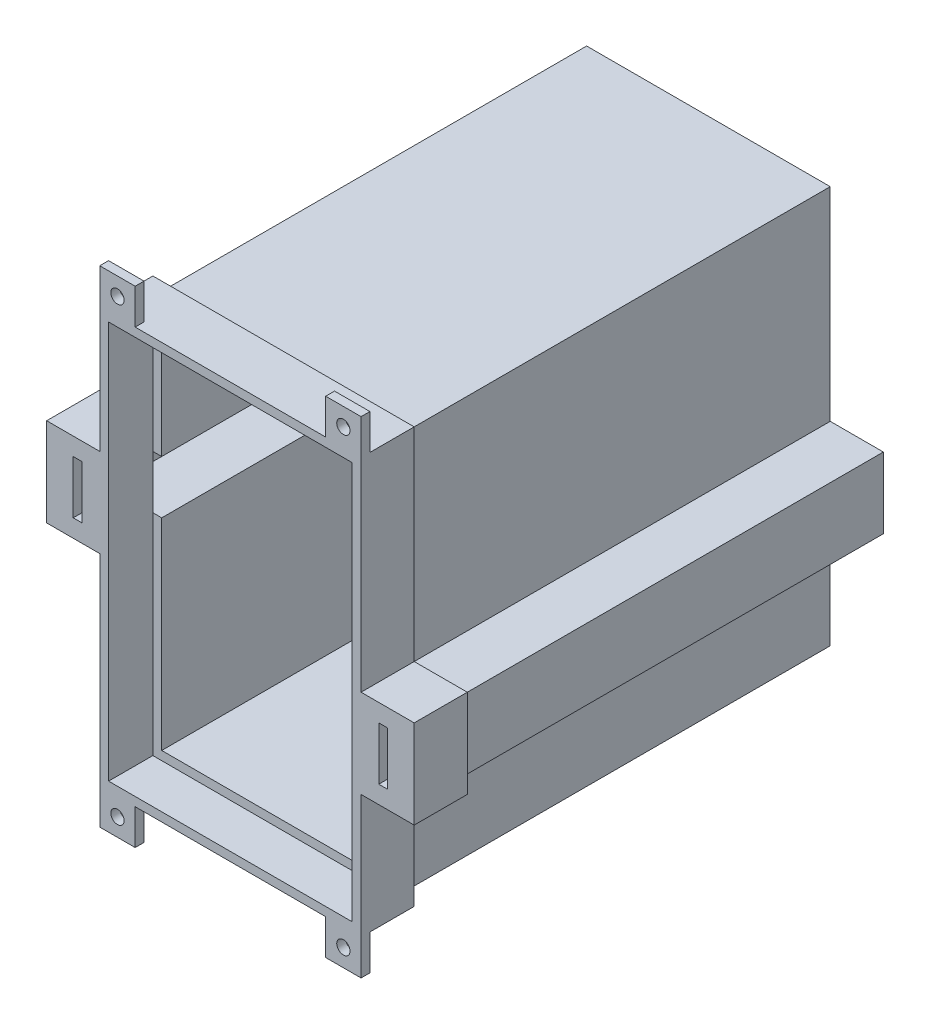
SolidWorks part; units mm, degrees
ref_plane "Front Plane" through (0, 0, 0) normal (0, 0, 1) x (1, 0, 0)
ref_plane "Top Plane" through (0, 0, 0) normal (0, 1, 0) x (1, 0, 0)
ref_plane "Right Plane" through (0, 0, 0) normal (1, 0, 0) x (0, 0, -1)
sketch "Sketch1" plane through (0, 0, 0) normal (0, 0, 1) x (1, 0, 0)
  line L0 (0, -71.3105) -> (0, 71.3105) construction
  line L1 (-43.688, 71.3105) -> (43.688, 71.3105)
  line L2 (-43.688, 71.3105) -> (-43.688, 26.3525)
  line L4 (43.688, 71.3105) -> (43.688, -1.5875)
  line L5 (-43.688, 71.3105) -> (43.688, -71.3105) construction
  line L6 (-43.688, -71.3105) -> (43.688, 71.3105) construction
  line L13 (-43.688, 26.3525) -> (-62.738, 26.3525)
  line L15 (-43.688, 0.9525) -> (-62.738, 0.9525)
  line L16 (-62.738, 26.3525) -> (-62.738, 0.9525)
  line L17 (43.688, -1.5875) -> (62.738, -1.5875)
  line L19 (43.688, -26.9875) -> (62.738, -26.9875)
  line L20 (62.738, -1.5875) -> (62.738, -26.9875)
  line L23 (-43.688, 0.9525) -> (-43.688, -71.3105)
  line L24 (43.688, -26.9875) -> (43.688, -71.3105)
  line L26 (-43.688, -71.3105) -> (43.688, -71.3105)
  point P0 (0, 0)
  dimension "D1" = 44.323
  dimension "D2" = 87.376
  dimension "D3" = 72.263
  dimension "D4" = 72.898
  dimension "D5" = 44.958
  dimension "D6" = 19.05
  dimension "D7" = 19.05
  dimension "D8" = 142.621
  dimension "D9" = 25.4
  dimension "D10" = 142.621
  dimension "D11" = 25.4
extrude "Boss-Extrude1" add sketch "Sketch1" against normal blind 155.575
shell "Shell1" thickness 3.175
sketch "Sketch2" plane through (-43.688, 0, 0) normal (-1, 0, 0) x (0, 0, 1)
  line L1 (-3.175, -71.3105) -> (15.875, -71.3105)
  line L2 (-3.175, -71.3105) -> (-3.175, 0.9525)
  line L3 (-3.175, 0.9525) -> (15.875, 0.9525)
  line L4 (15.875, -71.3105) -> (15.875, 0.9525)
  line L5 (-155.575, 0.9525) -> (0, 0.9525) construction
  line L6 (-155.575, 71.3105) -> (0, 71.3105) construction
  line L7 (-3.175, 26.3525) -> (15.875, 26.3525)
  line L8 (-3.175, 26.3525) -> (-3.175, 71.3105)
  line L9 (-3.175, 71.3105) -> (15.875, 71.3105)
  line L10 (15.875, 26.3525) -> (15.875, 71.3105)
  line L11 (-155.575, 26.3525) -> (0, 26.3525) construction
  line L12 (0, 0.9525) -> (0, -71.3105) construction
  dimension "D1" = 19.05
  dimension "D2" = 19.05
  dimension "D3" = 3.175
extrude "Boss-Extrude2" add sketch "Sketch2" along normal blind 3.175
sketch "Sketch5" plane through (0, -71.3105, 0) normal (0, -1, 0) x (1, 0, 0)
  line L1 (43.688, -3.175) -> (-46.863, -3.175)
  line L2 (43.688, -3.175) -> (43.688, 15.875)
  line L3 (43.688, 15.875) -> (-46.863, 15.875)
  line L4 (-46.863, -3.175) -> (-46.863, 15.875)
extrude "Boss-Extrude8" add sketch "Sketch5" along normal blind 3.175
sketch "Sketch7" plane through (43.688, 0, 0) normal (1, 0, 0) x (0, 0, -1)
  line L0 (155.575, -26.9875) -> (0, -26.9875) construction
  line L1 (3.175, -26.9875) -> (-15.875, -26.9875)
  line L2 (3.175, -26.9875) -> (3.175, -74.4855)
  line L3 (3.175, -74.4855) -> (-15.875, -74.4855)
  line L4 (-15.875, -26.9875) -> (-15.875, -74.4855)
extrude "ALL 6" add sketch "Sketch7" along normal blind 3.175
sketch "Sketch8" plane through (43.688, 0, 0) normal (1, 0, 0) x (0, 0, -1)
  line L0 (155.575, 71.3105) -> (0, 71.3105) construction
  line L1 (3.175, 71.3105) -> (-15.875, 71.3105)
  line L2 (3.175, 71.3105) -> (3.175, -1.5875)
  line L3 (3.175, -1.5875) -> (-15.875, -1.5875)
  line L4 (-15.875, 71.3105) -> (-15.875, -1.5875)
  line L5 (3.175, -74.4855) -> (3.175, -26.9875) construction
  line L6 (-15.875, -26.9875) -> (-15.875, -74.4855) construction
  line L7 (155.575, -1.5875) -> (0, -1.5875) construction
extrude "ALL 5" add sketch "Sketch8" along normal blind 3.175
sketch "Sketch9" plane through (0, 71.3105, 0) normal (0, 1, 0) x (1, 0, 0)
  line L0 (-46.863, -15.875) -> (-46.863, 3.175) construction
  line L1 (-46.863, 3.175) -> (46.863, 3.175)
  line L2 (-46.863, 3.175) -> (-46.863, -15.875)
  line L3 (-46.863, -15.875) -> (46.863, -15.875)
  line L4 (46.863, 3.175) -> (46.863, -15.875)
  dimension "D1" = 19.05
extrude "Boss-Extrude12" add sketch "Sketch9" along normal blind 3.175
sketch "Sketch10" plane through (0, -1.5875, 0) normal (0, 1, 0) x (1, 0, 0)
  line L8 (46.863, 3.175) -> (43.688, 3.175) construction
  line L9 (46.863, 3.175) -> (62.738, 3.175)
  line L10 (46.863, 3.175) -> (46.863, -15.875)
  line L11 (46.863, -15.875) -> (62.738, -15.875)
  line L12 (62.738, 3.175) -> (62.738, -15.875)
  line L13 (46.863, -15.875) -> (43.688, -15.875) construction
  line L14 (62.738, 155.575) -> (62.738, 0) construction
  line L16 (46.863, -15.875) -> (46.863, 0) construction
extrude "ALL2" add sketch "Sketch10" along normal blind 3.175
sketch "Sketch11" plane through (0, -26.9875, 0) normal (0, -1, 0) x (1, 0, 0)
  line L5 (46.863, 0) -> (62.738, 0) construction
  line L7 (46.863, 0) -> (46.863, 15.875) construction
  line L8 (62.738, -3.175) -> (46.863, -3.175)
  line L9 (62.738, -3.175) -> (62.738, 15.875)
  line L10 (62.738, 15.875) -> (46.863, 15.875)
  line L11 (46.863, -3.175) -> (46.863, 15.875)
  line L12 (46.863, 15.875) -> (43.688, 15.875) construction
  line L15 (62.738, -155.575) -> (62.738, 0) construction
  dimension "D1" = 3.175
extrude "ALL 7" add sketch "Sketch11" along normal blind 3.175
sketch "Sketch13" plane through (-62.738, 0, 0) normal (-1, 0, 0) x (0, 0, 1)
  line L0 (-155.575, 0.9525) -> (0, 0.9525) construction
  line L1 (-3.175, 0.9525) -> (15.875, 0.9525)
  line L2 (-3.175, 0.9525) -> (-3.175, 26.3525)
  line L3 (-3.175, 26.3525) -> (15.875, 26.3525)
  line L4 (15.875, 0.9525) -> (15.875, 26.3525)
  line L5 (-155.575, 26.3525) -> (0, 26.3525) construction
extrude "ALL" add sketch "Sketch13" along normal blind 3.175
sketch "Sketch27" plane through (0, 74.4855, -58.6105) normal (0, -1, 0) x (1, 0, 0)
  line L0 (-46.863, 74.4855) -> (46.863, 74.4855) construction
  line L1 (46.863, 71.3105) -> (34.163, 71.3105)
  line L3 (46.863, 74.4855) -> (34.163, 74.4855)
  line L4 (34.163, 71.3105) -> (34.163, 74.4855)
  line L8 (46.863, 71.3105) -> (46.863, 74.4855)
  line L9 (46.863, 74.4855) -> (46.863, 55.4355) construction
  dimension "D1" = 12.7
  dimension "D2" = 3.175
extrude "Boss-Extrude29" add sketch "Sketch27" against normal blind 12.7
sketch "Sketch28" plane through (0, 58.6105, 15.875) normal (0, 0, -1) x (1, 0, 0)
  line L0 (40.513, -28.575) -> (40.513, -15.875) construction
  line L1 (46.863, -28.575) -> (34.163, -28.575) construction
  line L2 (-46.863, -15.875) -> (34.163, -15.875) construction
  line L4 (0, -15.875) -> (0, -12.7) construction
  line L5 (46.863, -15.875) -> (-46.863, -15.875) construction
  line L6 (34.163, -22.225) -> (46.863, -22.225) construction
  line L7 (34.163, -28.575) -> (34.163, -15.875) construction
  line L8 (46.863, -28.575) -> (46.863, 57.023) construction
  line L9 (-43.688, -12.7) -> (43.688, -12.7) construction
  line L10 (46.863, -28.575) -> (34.163, -28.575) construction
  circle A0 centre (40.513, -22.225) radius 2.3812
  dimension "D1" = 6.35
  dimension "D3" = 4.7625
extrude "Cut-Extrude4" cut sketch "Sketch28" along normal through all
mirror "Mirror1" about plane through (0, 0, 0) normal (1, 0, 0) of "Boss-Extrude29", "Cut-Extrude4"
mirror "Mirror2" about plane through (0, 0, 0) normal (0, 1, 0) of "Boss-Extrude29", "Mirror1", "Cut-Extrude4"
sketch "Sketch31" plane through (-62.738, 0, 0) normal (1, 0, 0) x (0, 0, -1)
  line L0 (0, 26.3525) -> (0, 0.9525) construction
  line L1 (-15.875, 4.1275) -> (0, 4.1275)
  line L2 (-15.875, 4.1275) -> (-15.875, 26.3525)
  line L3 (-15.875, 26.3525) -> (0, 26.3525)
  line L4 (0, 4.1275) -> (0, 26.3525)
  line L5 (0, 26.3525) -> (-15.875, 26.3525) construction
extrude "Boss-Extrude31" add sketch "Sketch31" along normal blind 3.175
sketch "Sketch34" [suppressed] plane through (0, -71.3105, 0) normal (0, 1, 0) x (1, 0, 0)
  line L4 (43.688, 0) -> (-43.688, 0)
  line L5 (-43.688, 0) -> (-43.688, -15.875)
  line L6 (-43.688, -15.875) -> (43.688, -15.875)
  line L7 (43.688, -15.875) -> (43.688, 0)
  line L8 (43.688, 0) -> (-43.688, 0)
  line L9 (-43.688, 0) -> (-43.688, -15.875)
  line L10 (-43.688, -15.875) -> (43.688, -15.875)
  line L11 (43.688, -15.875) -> (43.688, 0)
  dimension "D1" = 0
extrude "Cut-Extrude6" [suppressed] cut sketch "Sketch34" against normal blind 0.254
sketch "Sketch35" [suppressed] plane through (43.688, 0, 0) normal (-1, 0, 0) x (0, 0, 1)
  line L4 (0, -27.2415) -> (0, -71.3105)
  line L5 (0, -27.2415) -> (0, -71.3105)
  line L6 (15.875, -71.3105) -> (15.875, -27.2415)
  line L7 (15.875, -27.2415) -> (0, -27.2415)
  line L10 (15.875, -71.3105) -> (15.875, -27.2415)
  line L11 (15.875, -27.2415) -> (0, -27.2415)
  line L12 (0, -71.3105) -> (15.875, -71.3105)
  line L13 (0, -71.3105) -> (15.875, -71.3105)
  dimension "D1" = 0
extrude "Cut-Extrude7" [suppressed] cut sketch "Sketch35" against normal blind 0.254
sketch "Sketch36" [suppressed] plane through (0, -27.2415, 0) normal (0, 1, 0) x (1, 0, 0)
  line L4 (43.688, 0) -> (43.688, -15.875)
  line L5 (43.688, -15.875) -> (62.992, -15.875)
  line L6 (62.992, -15.875) -> (62.992, 0)
  line L7 (62.992, 0) -> (43.688, 0)
  line L9 (43.688, -15.875) -> (62.992, -15.875)
  line L11 (62.992, 0) -> (43.688, 0)
  line L12 (43.688, 0) -> (43.688, -15.875)
  line L13 (62.992, -15.875) -> (62.992, 0)
  dimension "D1" = 0
extrude "Cut-Extrude8" [suppressed] cut sketch "Sketch36" against normal blind 0.254
sketch "Sketch38" [suppressed] plane through (0, -1.3335, 0) normal (0, -1, 0) x (1, 0, 0)
  line L4 (43.688, 15.875) -> (43.688, 0)
  line L5 (43.688, 0) -> (62.992, 0)
  line L6 (43.688, 0) -> (62.992, 0)
  line L7 (62.992, 15.875) -> (43.688, 15.875)
  line L8 (43.688, 15.875) -> (43.688, 0)
  line L11 (62.992, 15.875) -> (43.688, 15.875)
  line L12 (62.992, 0) -> (62.992, 15.875)
  line L14 (62.992, 0) -> (62.992, 15.875)
  dimension "D1" = 0
extrude "Cut-Extrude10" [suppressed] cut sketch "Sketch38" against normal blind 0.254
sketch "Sketch39" [suppressed] plane through (43.688, 0, 0) normal (-1, 0, 0) x (0, 0, 1)
  line L4 (0, 71.3105) -> (0, -1.3335)
  line L5 (0, -1.3335) -> (15.875, -1.3335)
  line L6 (15.875, -1.3335) -> (15.875, 71.3105)
  line L7 (15.875, 71.3105) -> (0, 71.3105)
  line L8 (0, 71.3105) -> (0, -1.3335)
  line L10 (15.875, -1.3335) -> (15.875, 71.3105)
  line L11 (15.875, 71.3105) -> (0, 71.3105)
  line L12 (0, -1.3335) -> (15.875, -1.3335)
  dimension "D1" = 0
extrude "Cut-Extrude11" [suppressed] cut sketch "Sketch39" against normal blind 0.254
sketch "Sketch40" [suppressed] plane through (0, 71.3105, 0) normal (0, -1, 0) x (1, 0, 0)
  line L4 (-43.688, 0) -> (43.688, 0)
  line L5 (-43.688, 0) -> (43.688, 0)
  line L6 (43.688, 15.875) -> (-43.688, 15.875)
  line L7 (-43.688, 15.875) -> (-43.688, 0)
  line L10 (43.688, 15.875) -> (-43.688, 15.875)
  line L11 (-43.688, 15.875) -> (-43.688, 0)
  line L12 (43.688, 0) -> (43.688, 15.875)
  line L13 (43.688, 0) -> (43.688, 15.875)
  dimension "D1" = 0
extrude "Cut-Extrude12" [suppressed] cut sketch "Sketch40" against normal blind 0.254
sketch "Sketch41" [suppressed] plane through (-43.688, 0, 0) normal (1, 0, 0) x (0, 0, -1)
  line L4 (0, 26.6065) -> (0, 71.3105)
  line L5 (0, 26.6065) -> (0, 71.3105)
  line L6 (-15.875, 71.3105) -> (-15.875, 26.6065)
  line L7 (-15.875, 26.6065) -> (0, 26.6065)
  line L11 (-15.875, 26.6065) -> (0, 26.6065)
  line L12 (0, 71.3105) -> (-15.875, 71.3105)
  line L13 (0, 71.3105) -> (-15.875, 71.3105)
  line L14 (-15.875, 71.3105) -> (-15.875, 26.6065)
  dimension "D1" = 0
extrude "Cut-Extrude13" [suppressed] cut sketch "Sketch41" against normal blind 0.254
sketch "Sketch42" [suppressed] plane through (0, 26.6065, 0) normal (0, -1, 0) x (1, 0, 0)
  line L4 (-43.688, 0) -> (-43.688, 15.875)
  line L5 (-46.863, 15.875) -> (-46.863, 0)
  line L6 (-46.863, 15.875) -> (-46.863, 0)
  line L7 (-46.863, 0) -> (-43.688, 0)
  line L11 (-46.863, 0) -> (-43.688, 0)
  line L12 (-43.688, 0) -> (-43.688, 15.875)
  line L13 (-43.688, 15.875) -> (-46.863, 15.875)
  line L14 (-43.688, 15.875) -> (-46.863, 15.875)
  dimension "D1" = 0
extrude "Cut-Extrude14" [suppressed] cut sketch "Sketch42" against normal blind 0.254
sketch "Sketch43" [suppressed] plane through (-62.992, 0, 0) normal (1, 0, 0) x (0, 0, -1)
  line L4 (0, 0.6985) -> (0, 26.6065)
  line L5 (0, 0.6985) -> (0, 26.6065)
  line L6 (-15.875, 26.6065) -> (-15.875, 0.6985)
  line L7 (0, 26.6065) -> (-15.875, 26.6065)
  line L10 (-15.875, 26.6065) -> (-15.875, 0.6985)
  line L12 (0, 26.6065) -> (-15.875, 26.6065)
  line L22 (-15.875, 0.6985) -> (0, 0.6985)
  line L23 (-15.875, 0.6985) -> (0, 0.6985)
  dimension "D1" = 0
extrude "Cut-Extrude15" [suppressed] cut sketch "Sketch43" against normal blind 0.254
sketch "Sketch44" [suppressed] plane through (0, 0.6985, 0) normal (0, 1, 0) x (1, 0, 0)
  line L4 (-43.688, -15.875) -> (-43.688, 0)
  line L5 (-43.688, 0) -> (-46.863, 0)
  line L6 (-43.688, 0) -> (-46.863, 0)
  line L7 (-46.863, -15.875) -> (-43.688, -15.875)
  line L8 (-43.688, -15.875) -> (-43.688, 0)
  line L11 (-46.863, -15.875) -> (-43.688, -15.875)
  line L12 (-46.863, 0) -> (-46.863, -15.875)
  line L14 (-46.863, 0) -> (-46.863, -15.875)
  dimension "D1" = 0
extrude "Cut-Extrude16" [suppressed] cut sketch "Sketch44" against normal blind 0.254
sketch "Sketch45" [suppressed] plane through (-43.688, 0, 0) normal (1, 0, 0) x (0, 0, -1)
  line L4 (0, -71.3105) -> (0, 0.6985)
  line L5 (0, -71.3105) -> (0, 0.6985)
  line L6 (-15.875, 0.6985) -> (-15.875, -71.3105)
  line L7 (0, 0.6985) -> (-15.875, 0.6985)
  line L10 (-15.875, 0.6985) -> (-15.875, -71.3105)
  line L12 (0, 0.6985) -> (-15.875, 0.6985)
  line L13 (-15.875, -71.3105) -> (0, -71.3105)
  line L14 (-15.875, -71.3105) -> (0, -71.3105)
  dimension "D1" = 0
extrude "Cut-Extrude17" [suppressed] cut sketch "Sketch45" against normal blind 0.254
ref_plane "Plane1" through (0, 0, -104.775) normal (0, 0, -1) x (-1, 0, 0)
sketch "Sketch46" [suppressed] plane through (0, 0, -104.775) normal (0, 0, -1) x (-1, 0, 0)
  line L1 (83.5804, 78.4798) -> (-82.1893, 78.4798)
  line L2 (83.5804, 78.4798) -> (83.5804, -84.7396)
  line L3 (83.5804, -84.7396) -> (-82.1893, -84.7396)
  line L4 (-82.1893, 78.4798) -> (-82.1893, -84.7396)
extrude "Cut-Extrude18" [suppressed] cut sketch "Sketch46" against normal through all
sketch "Sketch48" [suppressed] plane through (0, 0, -155.575) normal (0, 0, -1) x (-1, 0, 0)
  line L0 (41.402, 69.0245) -> (-41.402, 69.0245)
  line L1 (-41.402, 69.0245) -> (-41.402, 15.5575)
  line L2 (-41.402, 15.5575) -> (-73.66, 15.5575)
  line L3 (-73.66, 15.5575) -> (-73.66, -15.5321)
  line L4 (-73.66, -15.5321) -> (-41.402, -15.5321)
  line L5 (-41.402, -15.5321) -> (-41.402, -69.0245)
  line L6 (-41.402, -69.0245) -> (41.402, -69.0245)
  line L7 (41.402, -69.0245) -> (41.402, -15.5321)
  line L8 (41.402, -15.5321) -> (73.66, -15.5321)
  line L9 (73.66, -15.5321) -> (73.66, 15.5575)
  line L10 (73.66, 15.5575) -> (41.402, 15.5575)
  line L11 (41.402, 15.5575) -> (41.402, 69.0245)
extrude "Cut-Extrude21" [suppressed] cut sketch "Sketch48" against normal up to vertex
sketch "Sketch50" [suppressed] plane through (0, -71.3105, 0) normal (0, 1, 0) x (1, 0, 0)
  line L4 (43.688, 0) -> (-43.688, 0)
  line L5 (-43.688, 0) -> (-43.688, -15.875)
  line L6 (-43.688, -15.875) -> (43.688, -15.875)
  line L7 (43.688, -15.875) -> (43.688, 0)
  line L8 (43.688, 0) -> (-43.688, 0)
  line L9 (-43.688, 0) -> (-43.688, -15.875)
  line L10 (-43.688, -15.875) -> (43.688, -15.875)
  line L11 (43.688, -15.875) -> (43.688, 0)
  dimension "D1" = 0
extrude "Boss-Extrude34" [suppressed] add sketch "Sketch50" along normal blind 0.381
sketch "Sketch51" [suppressed] plane through (-43.688, 0, 0) normal (1, 0, 0) x (0, 0, -1)
  line L4 (-15.875, -70.9295) -> (0, -70.9295)
  line L5 (0, -70.9295) -> (0, 0.9525)
  line L6 (0, 0.9525) -> (-15.875, 0.9525)
  line L7 (-15.875, 0.9525) -> (-15.875, -70.9295)
  line L8 (-15.875, -70.9295) -> (0, -70.9295)
  line L9 (0, -70.9295) -> (0, 0.9525)
  line L10 (0, 0.9525) -> (-15.875, 0.9525)
  line L11 (-15.875, 0.9525) -> (-15.875, -70.9295)
  dimension "D1" = 0
extrude "Boss-Extrude35" [suppressed] add sketch "Sketch51" along normal blind 0.381
sketch "Sketch52" [suppressed] plane through (0, 0.9525, 0) normal (0, 1, 0) x (1, 0, 0)
  line L4 (-46.863, -15.875) -> (-43.307, -15.875)
  line L5 (-43.307, -15.875) -> (-43.307, 0)
  line L6 (-43.307, 0) -> (-46.863, 0)
  line L8 (-46.863, -15.875) -> (-43.307, -15.875)
  line L9 (-43.307, -15.875) -> (-43.307, 0)
  line L12 (-46.863, 0) -> (-46.863, -15.875)
  line L13 (-46.863, 0) -> (-46.863, -15.875)
  line L14 (-43.307, 0) -> (-46.863, 0)
  dimension "D1" = 0
extrude "Boss-Extrude36" [suppressed] add sketch "Sketch52" along normal blind 0.381
sketch "Sketch53" [suppressed] plane through (-56.388, 0, 0) normal (1, 0, 0) x (0, 0, -1)
  line L4 (-15.875, 0.9525) -> (0, 0.9525)
  line L5 (0, 0.9525) -> (0, 26.3525)
  line L6 (-15.875, 0.9525) -> (0, 0.9525)
  line L7 (-15.875, 26.3525) -> (-15.875, 0.9525)
  line L9 (0, 0.9525) -> (0, 26.3525)
  line L11 (-15.875, 26.3525) -> (-15.875, 0.9525)
  line L17 (0, 26.3525) -> (-15.875, 26.3525)
  line L18 (0, 26.3525) -> (-15.875, 26.3525)
  dimension "D1" = 0
extrude "Boss-Extrude37" [suppressed] add sketch "Sketch53" along normal blind 0.381
sketch "Sketch56" [suppressed] plane through (-43.688, 0, 0) normal (1, 0, 0) x (0, 0, -1)
  line L4 (0, 26.3525) -> (0, 71.3105)
  line L5 (0, 71.3105) -> (-15.875, 71.3105)
  line L6 (-15.875, 71.3105) -> (-15.875, 26.3525)
  line L7 (-15.875, 26.3525) -> (0, 26.3525)
  line L8 (0, 26.3525) -> (0, 71.3105)
  line L9 (0, 71.3105) -> (-15.875, 71.3105)
  line L12 (-15.875, 71.3105) -> (-15.875, 26.3525)
  line L17 (-15.875, 26.3525) -> (0, 26.3525)
  dimension "D1" = 0
extrude "Boss-Extrude39" [suppressed] add sketch "Sketch56" along normal blind 0.381
sketch "Sketch57" [suppressed] plane through (0, 71.3105, 0) normal (0, -1, 0) x (1, 0, 0)
  line L4 (43.688, 15.875) -> (-43.307, 15.875)
  line L5 (-43.307, 15.875) -> (-43.307, 0)
  line L6 (-43.307, 0) -> (43.688, 0)
  line L7 (43.688, 0) -> (43.688, 15.875)
  line L8 (43.688, 15.875) -> (-43.307, 15.875)
  line L9 (-43.307, 15.875) -> (-43.307, 0)
  line L10 (-43.307, 0) -> (43.688, 0)
  line L11 (43.688, 0) -> (43.688, 15.875)
  dimension "D1" = 0
extrude "Boss-Extrude40" [suppressed] add sketch "Sketch57" along normal blind 0.381
sketch "Sketch58" [suppressed] plane through (43.688, 0, 0) normal (-1, 0, 0) x (0, 0, 1)
  line L4 (15.875, 70.9295) -> (0, 70.9295)
  line L5 (0, 70.9295) -> (0, -1.5875)
  line L6 (0, -1.5875) -> (15.875, -1.5875)
  line L7 (15.875, -1.5875) -> (15.875, 70.9295)
  line L8 (15.875, 70.9295) -> (0, 70.9295)
  line L9 (0, 70.9295) -> (0, -1.5875)
  line L10 (0, -1.5875) -> (15.875, -1.5875)
  line L11 (15.875, -1.5875) -> (15.875, 70.9295)
  dimension "D1" = 0
extrude "Boss-Extrude41" [suppressed] add sketch "Sketch58" along normal blind 0.381
sketch "Sketch61" [suppressed] plane through (0, -26.9875, 0) normal (0, 1, 0) x (1, 0, 0)
  line L4 (43.688, -15.875) -> (56.388, -15.875)
  line L5 (56.388, -15.875) -> (56.388, 0)
  line L6 (56.388, 0) -> (43.688, 0)
  line L7 (43.688, 0) -> (43.688, -15.875)
  line L8 (43.688, -15.875) -> (56.388, -15.875)
  line L10 (56.388, 0) -> (43.688, 0)
  line L11 (43.688, 0) -> (43.688, -15.875)
  line L12 (56.388, -15.875) -> (56.388, 0)
  dimension "D1" = 0
extrude "Boss-Extrude44" [suppressed] add sketch "Sketch61" along normal blind 0.381
sketch "Sketch62" [suppressed] plane through (43.688, 0, 0) normal (-1, 0, 0) x (0, 0, 1)
  line L4 (0, -70.9295) -> (15.875, -70.9295)
  line L5 (15.875, -70.9295) -> (15.875, -26.9875)
  line L6 (15.875, -26.9875) -> (0, -26.9875)
  line L7 (0, -26.9875) -> (0, -70.9295)
  line L8 (0, -70.9295) -> (15.875, -70.9295)
  line L9 (15.875, -70.9295) -> (15.875, -26.9875)
  line L11 (0, -26.9875) -> (0, -70.9295)
  line L12 (15.875, -26.9875) -> (0, -26.9875)
  dimension "D1" = 0
extrude "Boss-Extrude45" [suppressed] add sketch "Sketch62" along normal blind 0.381
sketch "Sketch49" [suppressed] plane through (0, 0, -155.575) normal (0, 0, -1) x (-1, 0, 0)
  line L1 (-41.402, -15.5321) -> (-41.402, -69.0245)
  line L2 (-41.402, -69.0245) -> (41.402, -69.0245)
  line L3 (41.402, -69.0245) -> (41.402, -15.5321)
  line L4 (41.402, -15.5321) -> (73.66, -15.5321)
  line L5 (73.66, -15.5321) -> (73.66, 15.5575)
  line L6 (73.66, 15.5575) -> (41.402, 15.5575)
  line L7 (41.402, 15.5575) -> (41.402, 69.0245)
  line L8 (41.402, 69.0245) -> (-41.402, 69.0245)
  line L9 (-41.402, 69.0245) -> (-41.402, 15.5575)
  line L10 (-41.402, 15.5575) -> (-73.66, 15.5575)
  line L11 (-73.66, 15.5575) -> (-73.66, -15.5321)
  line L36 (-73.66, -15.5321) -> (-41.402, -15.5321)
extrude "Boss-Extrude33" [suppressed] add sketch "Sketch49" against normal blind 3.175
sketch "Sketch64" [suppressed] plane through (0, 0, 15.875) normal (0, 0, 1) x (1, 0, 0)
  line L0 (-43.307, -70.9295) -> (43.307, -70.9295)
  line L1 (43.307, -70.9295) -> (43.307, -17.4371)
  line L2 (43.307, -17.4371) -> (75.565, -17.4371)
  line L3 (75.565, -17.4371) -> (75.565, 17.4625)
  line L4 (75.565, 17.4625) -> (43.307, 17.4625)
  line L5 (43.307, 17.4625) -> (43.307, 70.9295)
  line L6 (43.307, 70.9295) -> (-43.307, 70.9295)
  line L7 (-43.307, 70.9295) -> (-43.307, 17.4625)
  line L8 (-43.307, 17.4625) -> (-75.565, 17.4625)
  line L9 (-75.565, 17.4625) -> (-75.565, -17.4371)
  line L10 (-75.565, -17.4371) -> (-43.307, -17.4371)
  line L11 (-43.307, -17.4371) -> (-43.307, -70.9295)
  line L36 (46.863, -74.4855) -> (-46.863, -74.4855) construction
  dimension "D1" = 3.556
extrude "Cut-Extrude22" [suppressed] cut sketch "Sketch64" against normal blind 15.875
sketch "Sketch87" plane through (62.738, 0, 0) normal (1, 0, 0) x (0, 0, -1)
  line L1 (-15.875, -30.1625) -> (3.175, -30.1625)
  line L2 (-15.875, -30.1625) -> (-15.875, 1.5875)
  line L3 (-15.875, 1.5875) -> (3.175, 1.5875)
  line L4 (3.175, -30.1625) -> (3.175, 1.5875)
extrude "ALL3" add sketch "Sketch87" along normal blind 3.175
sketch "Sketch89" plane through (-62.738, 0, 0) normal (1, 0, 0) x (0, 0, -1)
  line L4 (0, 0.9525) -> (0, 4.1275)
  line L5 (-15.875, 4.1275) -> (-15.875, 0.9525)
  line L6 (-15.875, 0.9525) -> (0, 0.9525)
  line L7 (0, 0.9525) -> (0, 4.1275)
  line L9 (-15.875, 4.1275) -> (-15.875, 0.9525)
  line L12 (0, 4.1275) -> (-15.875, 4.1275)
  line L13 (0, 4.1275) -> (-15.875, 4.1275)
  line L14 (-15.875, 0.9525) -> (0, 0.9525)
  dimension "D1" = 0
extrude "Boss-Extrude47" [suppressed] add sketch "Sketch89" along normal up to vertex
sketch "Sketch90" plane through (-62.738, 0, 0) normal (1, 0, 0) x (0, 0, -1)
  line L4 (-15.875, 4.1275) -> (-15.875, 0.9525)
  line L5 (0, 0.9525) -> (0, 4.1275)
  line L6 (0, 0.9525) -> (0, 4.1275)
  line L7 (0, 4.1275) -> (-15.875, 4.1275)
  line L8 (-15.875, 4.1275) -> (-15.875, 0.9525)
  line L12 (0, 4.1275) -> (-15.875, 4.1275)
  line L13 (-15.875, 0.9525) -> (0, 0.9525)
  line L14 (-15.875, 0.9525) -> (0, 0.9525)
  dimension "D1" = 0
extrude "Boss-Extrude48" [suppressed] add sketch "Sketch90" along normal up to vertex
sketch "Sketch91" plane through (-59.563, 0, 0) normal (1, 0, 0) x (0, 0, -1)
  line L0 (0, 0.9525) -> (-15.875, 0.9525) construction
  line L1 (-15.875, 0.9525) -> (0, 0.9525)
  line L2 (-15.875, 0.9525) -> (-15.875, 26.3525)
  line L3 (-15.875, 26.3525) -> (0, 26.3525)
  line L4 (0, 0.9525) -> (0, 26.3525)
extrude "ALL 4" cut sketch "Sketch91" against normal blind 3.175
sketch "Sketch92" [suppressed] plane through (62.992, 0, 0) normal (1, 0, 0) x (0, 0, -1)
  line L1 (-15.875, -30.4165) -> (3.175, -30.4165)
  line L2 (-15.875, -30.4165) -> (-15.875, 1.8415)
  line L3 (-15.875, 1.8415) -> (3.175, 1.8415)
  line L4 (3.175, -30.4165) -> (3.175, 1.8415)
extrude "Boss-Extrude49" [suppressed] add sketch "Sketch92" along normal blind 3.175
sketch "Sketch93" [suppressed] plane through (-61.7855, 0.6985, 0) normal (0, 1, 0) x (0, 0, -1)
  line L1 (-15.875, -14.9225) -> (3.175, -14.9225)
  line L2 (-15.875, -14.9225) -> (-15.875, 4.3815)
  line L3 (-15.875, 4.3815) -> (3.175, 4.3815)
  line L4 (3.175, -14.9225) -> (3.175, 4.3815)
  line L7 (-15.875, -14.9225) -> (0, -14.9225) construction
  line L8 (3.175, 4.3815) -> (-15.875, 4.3815) construction
  line L9 (3.175, 4.3815) -> (3.175, 1.2065) construction
  line L10 (-15.875, 4.3815) -> (-15.875, 1.2065) construction
extrude "Boss-Extrude51" [suppressed] add sketch "Sketch93" against normal blind 3.175
sketch "Sketch94" [suppressed] plane through (-89.0905, 26.6065, 0) normal (0, -1, 0) x (0, 0, -1)
  line L1 (3.175, 42.2275) -> (-15.875, 42.2275)
  line L2 (3.175, 42.2275) -> (3.175, 22.9235)
  line L3 (3.175, 22.9235) -> (-15.875, 22.9235)
  line L4 (-15.875, 42.2275) -> (-15.875, 22.9235)
  line L5 (-15.875, 22.9235) -> (3.175, 22.9235) construction
  line L6 (0, 42.2275) -> (-15.875, 42.2275) construction
  line L7 (-15.875, 22.9235) -> (-15.875, 26.0985) construction
  line L8 (3.175, 22.9235) -> (3.175, 26.0985) construction
extrude "Boss-Extrude52" [suppressed] add sketch "Sketch94" against normal blind 3.175
sketch "Sketch95" [suppressed] plane through (0, 0, -152.4) normal (0, 0, 1) x (1, 0, 0)
  line L0 (-43.688, -15.5321) -> (-73.66, -15.5321) construction
  line L1 (-73.66, 15.5575) -> (-56.388, 15.5575)
  line L2 (-73.66, 15.5575) -> (-73.66, -15.5321)
  line L3 (-73.66, -15.5321) -> (-56.388, -15.5321)
  line L4 (-56.388, 15.5575) -> (-56.388, -15.5321)
  line L5 (73.66, -15.5321) -> (56.388, -15.5321) construction
  line L6 (73.66, 15.5575) -> (56.388, 15.5575)
  line L7 (73.66, 15.5575) -> (73.66, -15.5321)
  line L8 (73.66, -15.5321) -> (56.388, -15.5321)
  line L9 (56.388, 15.5575) -> (56.388, -15.5321)
  dimension "D1" = 17.272
  dimension "D2" = 17.272
extrude "Cut-Extrude23" [suppressed] cut sketch "Sketch95" against normal through all
sketch "Sketch97" [suppressed] plane through (-88.7095, 26.3525, 0) normal (0, -1, 0) x (0, 0, -1)
  line L0 (-15.875, 29.1465) -> (3.175, 29.1465) construction
  line L1 (-15.875, 41.8465) -> (3.175, 41.8465)
  line L2 (-15.875, 41.8465) -> (-15.875, 29.1465)
  line L3 (-15.875, 29.1465) -> (3.175, 29.1465)
  line L4 (3.175, 41.8465) -> (3.175, 29.1465)
  line L5 (0, 41.8465) -> (-15.875, 41.8465) construction
  line L6 (-15.875, 29.1465) -> (-15.875, 32.7025) construction
  line L7 (3.175, 29.1465) -> (3.175, 32.3215) construction
extrude "Boss-Extrude54" [suppressed] add sketch "Sketch97" against normal blind 3.175
sketch "Sketch98" [suppressed] plane through (-61.4045, 0.9525, 0) normal (0, 1, 0) x (0, 0, -1)
  line L1 (3.175, -14.5415) -> (-15.875, -14.5415)
  line L2 (3.175, -14.5415) -> (3.175, -1.8415)
  line L3 (3.175, -1.8415) -> (-15.875, -1.8415)
  line L4 (-15.875, -14.5415) -> (-15.875, -1.8415)
  line L6 (-15.875, -14.5415) -> (0, -14.5415) construction
  line L7 (3.175, -1.8415) -> (-15.875, -1.8415) construction
  line L8 (3.175, -1.8415) -> (3.175, -5.0165) construction
  line L9 (-15.875, -1.8415) -> (-15.875, -5.3975) construction
extrude "Boss-Extrude55" [suppressed] add sketch "Sketch98" against normal blind 3.175
sketch "Sketch99" [suppressed] plane through (56.388, 0, 0) normal (1, 0, 0) x (0, 0, -1)
  line L1 (-15.875, -30.1625) -> (3.175, -30.1625)
  line L2 (-15.875, -30.1625) -> (-15.875, -1.5875)
  line L3 (-15.875, -1.5875) -> (3.175, -1.5875)
  line L4 (3.175, -30.1625) -> (3.175, -1.5875)
sketch "Sketch100" [suppressed] plane through (56.388, 0, 0) normal (1, 0, 0) x (0, 0, -1)
  line L0 (-15.875, 1.5875) -> (3.175, 1.5875) construction
  line L1 (-15.875, -30.1625) -> (3.175, -30.1625)
  line L2 (-15.875, -30.1625) -> (-15.875, 1.5875)
  line L3 (-15.875, 1.5875) -> (3.175, 1.5875)
  line L4 (3.175, -30.1625) -> (3.175, 1.5875)
  line L5 (3.175, 1.5875) -> (3.175, -1.5875) construction
extrude "Boss-Extrude57" [suppressed] add sketch "Sketch100" along normal blind 3.175
sketch "Sketch101" plane through (0, 0, -152.4) normal (0, 0, 1) x (1, 0, 0)
  line L12 (-40.513, -68.1355) -> (40.513, -68.1355)
  line L13 (40.513, -68.1355) -> (40.513, -23.8125)
  line L14 (40.513, -23.8125) -> (59.563, -23.8125)
  line L15 (59.563, -23.8125) -> (59.563, -4.7625)
  line L16 (59.563, -4.7625) -> (40.513, -4.7625)
  line L17 (40.513, -4.7625) -> (40.513, 68.1355)
  line L18 (40.513, 68.1355) -> (-40.513, 68.1355)
  line L19 (-40.513, 68.1355) -> (-40.513, 23.1775)
  line L20 (-40.513, 23.1775) -> (-59.563, 23.1775)
  line L21 (-59.563, 23.1775) -> (-59.563, 4.1275)
  line L22 (-59.563, 4.1275) -> (-40.513, 4.1275)
  line L23 (-40.513, 4.1275) -> (-40.513, -68.1355)
  line L24 (-40.513, -68.1355) -> (40.513, -68.1355)
  line L25 (40.513, -68.1355) -> (40.513, -23.8125)
  line L26 (40.513, -23.8125) -> (59.563, -23.8125)
  line L27 (59.563, -23.8125) -> (59.563, -4.7625)
  line L28 (59.563, -4.7625) -> (40.513, -4.7625)
  line L29 (40.513, -4.7625) -> (40.513, 68.1355)
  line L30 (40.513, 68.1355) -> (-40.513, 68.1355)
  line L31 (-40.513, 68.1355) -> (-40.513, 23.1775)
  line L32 (-40.513, 23.1775) -> (-59.563, 23.1775)
  line L33 (-59.563, 23.1775) -> (-59.563, 4.1275)
  line L34 (-59.563, 4.1275) -> (-40.513, 4.1275)
  line L35 (-40.513, 4.1275) -> (-40.513, -68.1355)
  dimension "D1" = 0
extrude "Cut-Extrude24" cut sketch "Sketch101" against normal through all
sketch "Sketch102" plane through (0, 26.3525, 0) normal (0, 1, 0) x (1, 0, 0)
  line L1 (-46.863, 3.175) -> (-65.913, 3.175)
  line L2 (-46.863, 3.175) -> (-46.863, -15.875)
  line L3 (-46.863, -15.875) -> (-65.913, -15.875)
  line L4 (-65.913, 3.175) -> (-65.913, -15.875)
extrude "Boss-Extrude58" add sketch "Sketch102" along normal blind 3.175
sketch "Sketch103" plane through (0, 0.9525, 0) normal (0, -1, 0) x (1, 0, 0)
  line L1 (-65.913, 15.875) -> (-46.863, 15.875)
  line L2 (-65.913, 15.875) -> (-65.913, -3.175)
  line L3 (-65.913, -3.175) -> (-46.863, -3.175)
  line L4 (-46.863, 15.875) -> (-46.863, -3.175)
  dimension "D1" = 19.05
extrude "Boss-Extrude59" add sketch "Sketch103" along normal blind 3.175
sketch "Sketch105" plane through (-43.688, 0, 0) normal (1, 0, 0) x (0, 0, -1)
  line L1 (-15.875, 0.9525) -> (0, 0.9525)
  line L2 (-15.875, 0.9525) -> (-15.875, 26.3525)
  line L3 (-15.875, 26.3525) -> (0, 26.3525)
  line L4 (0, 0.9525) -> (0, 26.3525)
extrude "Boss-Extrude65" add sketch "Sketch105" against normal blind 9.525
sketch "Sketch106" plane through (43.688, 0, 0) normal (-1, 0, 0) x (0, 0, 1)
  line L1 (15.875, -1.5875) -> (0, -1.5875)
  line L2 (15.875, -1.5875) -> (15.875, -26.9875)
  line L3 (15.875, -26.9875) -> (0, -26.9875)
  line L4 (0, -1.5875) -> (0, -26.9875)
extrude "Boss-Extrude66" add sketch "Sketch106" against normal blind 9.525
sketch "Sketch107" plane through (62.738, 0, 0) normal (-1, 0, 0) x (0, 0, 1)
  line L4 (0, -1.5875) -> (0, -26.9875)
  line L5 (0, -26.9875) -> (15.875, -26.9875)
  line L6 (15.875, -26.9875) -> (15.875, -1.5875)
  line L7 (15.875, -1.5875) -> (0, -1.5875)
  line L8 (0, -1.5875) -> (0, -26.9875)
  line L9 (0, -26.9875) -> (15.875, -26.9875)
  line L10 (15.875, -26.9875) -> (15.875, -1.5875)
  line L11 (15.875, -1.5875) -> (0, -1.5875)
  dimension "D1" = 0
extrude "Boss-Extrude67" add sketch "Sketch107" along normal blind 6.35
sketch "Sketch108" plane through (-62.738, 0, 0) normal (1, 0, 0) x (0, 0, -1)
  line L4 (0, 0.9525) -> (0, 26.3525)
  line L6 (-15.875, 26.3525) -> (-15.875, 0.9525)
  line L10 (-15.875, 26.3525) -> (-15.875, 0.9525)
  line L20 (-15.875, 0.9525) -> (0, 0.9525)
  line L21 (-15.875, 0.9525) -> (0, 0.9525)
  line L22 (0, 0.9525) -> (0, 26.3525)
  line L24 (0, 26.3525) -> (-15.875, 26.3525)
  line L25 (0, 26.3525) -> (-15.875, 26.3525)
  dimension "D1" = 0
extrude "Boss-Extrude68" add sketch "Sketch108" along normal blind 6.35
sketch "Sketch109" plane through (0, 0.9525, 0) normal (0, 1, 0) x (1, 0, 0)
  line L4 (-53.213, 0) -> (-56.388, 0)
  line L5 (-56.388, 0) -> (-56.388, -15.875)
  line L6 (-56.388, -15.875) -> (-53.213, -15.875)
  line L8 (-53.213, 0) -> (-56.388, 0)
  line L10 (-56.388, -15.875) -> (-53.213, -15.875)
  line L12 (-56.388, 0) -> (-56.388, -15.875)
  line L16 (-53.213, -15.875) -> (-53.213, 0)
  line L17 (-53.213, -15.875) -> (-53.213, 0)
  dimension "D1" = 0
extrude "Boss-Extrude69" add sketch "Sketch109" along normal up to vertex
sketch "Sketch110" plane through (0, 26.3525, 0) normal (0, -1, 0) x (1, 0, 0)
  line L4 (-53.213, 15.875) -> (-56.388, 15.875)
  line L5 (-56.388, 15.875) -> (-56.388, 0)
  line L6 (-56.388, 0) -> (-53.213, 0)
  line L8 (-53.213, 15.875) -> (-56.388, 15.875)
  line L10 (-56.388, 0) -> (-53.213, 0)
  line L14 (-53.213, 0) -> (-53.213, 15.875)
  line L15 (-53.213, 0) -> (-53.213, 15.875)
  line L17 (-56.388, 15.875) -> (-56.388, 0)
  dimension "D1" = 0
extrude "Boss-Extrude70" add sketch "Sketch110" along normal up to vertex
sketch "Sketch111" plane through (0, -1.5875, 0) normal (0, -1, 0) x (1, 0, 0)
  line L4 (53.213, 0) -> (56.388, 0)
  line L5 (56.388, 0) -> (56.388, 15.875)
  line L6 (56.388, 15.875) -> (53.213, 15.875)
  line L8 (53.213, 0) -> (56.388, 0)
  line L10 (56.388, 15.875) -> (53.213, 15.875)
  line L12 (56.388, 0) -> (56.388, 15.875)
  line L14 (53.213, 15.875) -> (53.213, 0)
  line L15 (53.213, 15.875) -> (53.213, 0)
  dimension "D1" = 0
extrude "Boss-Extrude71" add sketch "Sketch111" along normal up to vertex
sketch "Sketch112" plane through (0, -26.9875, 0) normal (0, 1, 0) x (1, 0, 0)
  line L4 (53.213, -15.875) -> (56.388, -15.875)
  line L5 (56.388, -15.875) -> (56.388, 0)
  line L6 (56.388, 0) -> (53.213, 0)
  line L8 (53.213, -15.875) -> (56.388, -15.875)
  line L10 (56.388, 0) -> (53.213, 0)
  line L12 (56.388, -15.875) -> (56.388, 0)
  line L14 (53.213, 0) -> (53.213, -15.875)
  line L15 (53.213, 0) -> (53.213, -15.875)
  dimension "D1" = 0
extrude "Boss-Extrude72" add sketch "Sketch112" along normal up to vertex
